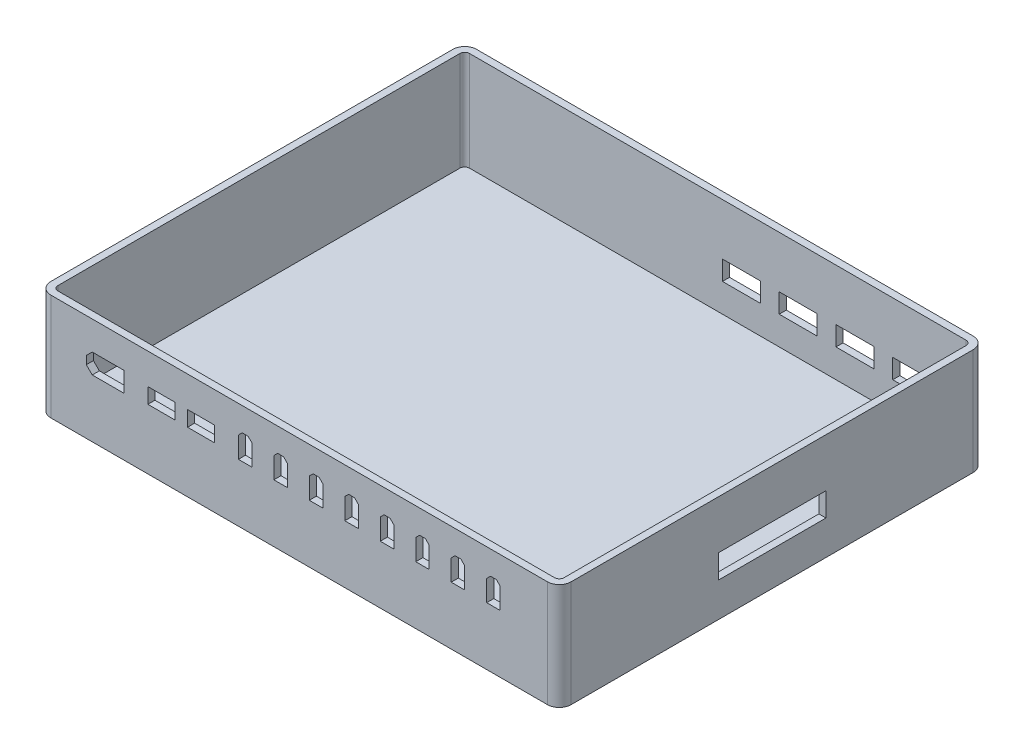
SolidWorks part; units mm, degrees
ref_plane "Front Plane" through (0, 0, 0) normal (0, 0, 1) x (1, 0, 0)
ref_plane "Top Plane" through (0, 0, 0) normal (0, 1, 0) x (1, 0, 0)
ref_plane "Right Plane" through (0, 0, 0) normal (1, 0, 0) x (0, 0, -1)
sketch "Sketch1" plane through (0, 0, 0) normal (0, 1, 0) x (1, 0, 0)
  line L1 (0, 0) -> (220, 0)
  line L2 (0, 0) -> (0, 180)
  line L3 (0, 180) -> (220, 180)
  line L4 (220, 0) -> (220, 180)
  dimension "D1" = 220
  dimension "D2" = 180
extrude "Boss-Extrude1" add sketch "Sketch1" along normal blind 45
fillet "Fillet1" radius 5 4 edges at (0, 22.5, -180) (0, 22.5, 0) (220, 22.5, -180) (220, 22.5, 0)
shell "Shell1" thickness 3
sketch "Sketch2" plane through (0, 0, 0) normal (0, 0, 1) x (1, 0, 0)
  line L0 (175.9, 35) -> (178.4, 35)
  line L1 (190.9, 35) -> (193.4, 35)
  line L2 (189.3, 33.4) -> (189.3, 24.5)
  line L3 (189.3, 24.5) -> (195, 24.5)
  line L4 (195, 33.4) -> (195, 24.5)
  line L5 (174.3, 33.4) -> (174.3, 24.5)
  line L6 (174.3, 24.5) -> (180, 24.5)
  line L7 (180, 33.4) -> (180, 24.5)
  line L8 (160.9, 35) -> (163.4, 35)
  line L9 (159.3, 33.4) -> (159.3, 24.5)
  line L10 (159.3, 24.5) -> (165, 24.5)
  line L11 (165, 33.4) -> (165, 24.5)
  line L12 (145.9, 35) -> (148.4, 35)
  line L13 (144.3, 33.4) -> (144.3, 24.5)
  line L14 (144.3, 24.5) -> (150, 24.5)
  line L15 (150, 33.4) -> (150, 24.5)
  line L16 (130.9, 35) -> (133.4, 35)
  line L17 (129.3, 33.4) -> (129.3, 24.5)
  line L18 (129.3, 24.5) -> (135, 24.5)
  line L19 (135, 33.4) -> (135, 24.5)
  line L20 (115.9, 35) -> (118.4, 35)
  line L21 (114.3, 33.4) -> (114.3, 24.5)
  line L22 (114.3, 24.5) -> (120, 24.5)
  line L23 (120, 33.4) -> (120, 24.5)
  line L24 (100.9, 35) -> (103.4, 35)
  line L25 (99.3, 33.4) -> (99.3, 24.5)
  line L26 (99.3, 24.5) -> (105, 24.5)
  line L27 (105, 33.4) -> (105, 24.5)
  line L28 (85.9, 35) -> (88.4, 35)
  line L29 (84.3, 33.4) -> (84.3, 24.5)
  line L30 (84.3, 24.5) -> (90, 24.5)
  line L31 (90, 33.4) -> (90, 24.5)
  line L32 (189.3, 35) -> (174.3, 35) construction
  line L33 (215, 0) -> (215, 45) construction
  line L35 (189.3, 33.4) -> (190.9, 35)
  line L36 (193.4, 35) -> (195, 33.4)
  line L37 (178.4, 35) -> (180, 33.4)
  line L38 (174.3, 33.4) -> (175.9, 35)
  line L39 (163.4, 35) -> (165, 33.4)
  line L40 (159.3, 33.4) -> (160.9, 35)
  line L41 (144.3, 33.4) -> (145.9, 35)
  line L42 (148.4, 35) -> (150, 33.4)
  line L43 (133.4, 35) -> (135, 33.4)
  line L44 (129.3, 33.4) -> (130.9, 35)
  line L45 (118.4, 35) -> (120, 33.4)
  line L46 (114.3, 33.4) -> (115.9, 35)
  line L47 (103.4, 35) -> (105, 33.4)
  line L48 (99.3, 33.4) -> (100.9, 35)
  line L49 (88.4, 35) -> (90, 33.4)
  line L50 (84.3, 33.4) -> (85.9, 35)
  line L51 (5, 0) -> (215, 0) construction
  point P0 (189.3, 35)
  point P3 (195, 35)
  point P6 (174.3, 35)
  point P9 (180, 35)
  point P10 (159.3, 35)
  point P13 (165, 35)
  point P14 (144.3, 35)
  point P17 (150, 35)
  point P18 (129.3, 35)
  point P21 (135, 35)
  point P22 (114.3, 35)
  point P25 (120, 35)
  point P26 (99.3, 35)
  point P29 (105, 35)
  point P30 (84.3, 35)
  point P33 (90, 35)
  point P39 (0, 0)
  dimension "D1" = 5.7
  dimension "D2" = 10.5
  dimension "D4" = 15
  dimension "D5" = 20
  dimension "D6" = 1.6
  dimension "D7" = 45
  dimension "D8" = 1.6
  dimension "D9" = 45
  dimension "D10" = 1.6
  dimension "D11" = 45
  dimension "D12" = 1.6
  dimension "D13" = 45
  dimension "D14" = 1.6
  dimension "D15" = 45
  dimension "D16" = 1.6
  dimension "D17" = 45
  dimension "D18" = 1.6
  dimension "D19" = 45
  dimension "D20" = 1.6
  dimension "D21" = 45
  dimension "D22" = 1.6
  dimension "D23" = 45
  dimension "D24" = 1.6
  dimension "D25" = 45
  dimension "D26" = 1.6
  dimension "D27" = 45
  dimension "D28" = 1.6
  dimension "D29" = 45
  dimension "D30" = 1.6
  dimension "D31" = 45
  dimension "D32" = 1.6
  dimension "D33" = 45
  dimension "D34" = 1.6
  dimension "D35" = 45
  dimension "D36" = 1.6
  dimension "D37" = 45
  dimension "D3" = 8
sketch "Sketch3" plane through (0, 0, 0) normal (0, 0, 1) x (1, 0, 0)
  line L0 (22.5, 32.9) -> (36, 32.9)
  line L1 (20, 30.4) -> (20, 27)
  line L2 (22.5, 24.5) -> (36, 24.5)
  line L3 (36, 32.9) -> (36, 24.5)
  line L4 (20, 30.4) -> (22.5, 32.9)
  line L5 (20, 27) -> (22.5, 24.5)
  line L6 (5, 0) -> (215, 0) construction
  line L7 (5, 45) -> (5, 0) construction
  point P0 (20, 32.9)
  point P2 (20, 24.5)
  dimension "D1" = 8.4
  dimension "D2" = 16
  dimension "D3" = 16
  dimension "D4" = 2.5
  dimension "D5" = 45
  dimension "D6" = 2.5
  dimension "D7" = 45
  dimension "D8" = 24.5
  dimension "D9" = 15
extrude "Cut-Extrude2" cut sketch "Sketch2" against normal blind 5
extrude "Cut-Extrude3" cut sketch "Sketch3" against normal blind 5
sketch "Sketch4" plane through (0, 0, 0) normal (0, 0, 1) x (1, 0, 0)
  line L0 (5, 0) -> (215, 0) construction
  line L1 (46, 25.5) -> (57.5, 25.5)
  line L2 (46, 25.5) -> (46, 32)
  line L3 (46, 32) -> (57.5, 32)
  line L4 (57.5, 25.5) -> (57.5, 32)
  line L5 (62.8, 25.5) -> (74.3, 25.5)
  line L6 (62.8, 25.5) -> (62.8, 32)
  line L7 (62.8, 32) -> (74.3, 32)
  line L8 (74.3, 25.5) -> (74.3, 32)
  line L9 (50.0473, 25.5) -> (65.0473, 25.5) construction
  line L10 (36, 24.5) -> (36, 32.9) construction
  line L11 (84.3, 33.4) -> (84.3, 24.5) construction
  dimension "D1" = 6.5
  dimension "D2" = 11.5
  dimension "D3" = 25.5
  dimension "D5" = 15
  dimension "D6" = 10
  dimension "D7" = 6.5
  dimension "D8" = 10
  dimension "D4" = 2
extrude "Cut-Extrude4" cut sketch "Sketch4" against normal blind 5
sketch "Sketch5" plane through (220, 0, 0) normal (1, 0, 0) x (0, 0, -1)
  line L0 (175, 0) -> (175, 45) construction
  line L5 (67.2316, 14.4802) -> (112.7684, 14.4802)
  line L7 (67.2316, 14.4802) -> (67.2316, 24.4802)
  line L8 (67.2316, 24.4802) -> (112.7684, 24.4802)
  line L9 (112.7684, 14.4802) -> (112.7684, 24.4802)
  line L10 (5, 45) -> (5, 0) construction
  dimension "D2" = 10
  dimension "D4" = 17.8646
extrude "Cut-Extrude5" cut sketch "Sketch5" against normal blind 5
sketch "Sketch6" plane through (0, 0, -180) normal (0, 0, -1) x (-1, 0, 0)
  line L0 (-215, 45) -> (-215, 0) construction
  line L1 (-200, 23.2) -> (-184, 23.2)
  line L2 (-200, 23.2) -> (-200, 15)
  line L3 (-200, 15) -> (-184, 15)
  line L4 (-184, 23.2) -> (-184, 15)
  line L5 (-215, 0) -> (-5, 0) construction
  line L6 (-176, 23.2) -> (-160, 23.2)
  line L7 (-176, 23.2) -> (-176, 15)
  line L8 (-176, 15) -> (-160, 15)
  line L9 (-160, 23.2) -> (-160, 15)
  line L10 (-152, 23.2) -> (-136, 23.2)
  line L11 (-152, 23.2) -> (-152, 15)
  line L12 (-152, 15) -> (-136, 15)
  line L13 (-136, 23.2) -> (-136, 15)
  line L14 (-128, 23.2) -> (-112, 23.2)
  line L15 (-128, 23.2) -> (-128, 15)
  line L16 (-128, 15) -> (-112, 15)
  line L17 (-112, 23.2) -> (-112, 15)
  line L18 (-200, 23.2) -> (-176, 23.2) construction
  dimension "D1" = 16
  dimension "D2" = 8.2
  dimension "D3" = 15
  dimension "D4" = 15
  dimension "D6" = 24
  dimension "D5" = 4
extrude "Cut-Extrude6" cut sketch "Sketch6" against normal blind 5
equation "\"D8@Sketch4\"=\"D6@Sketch4\""
